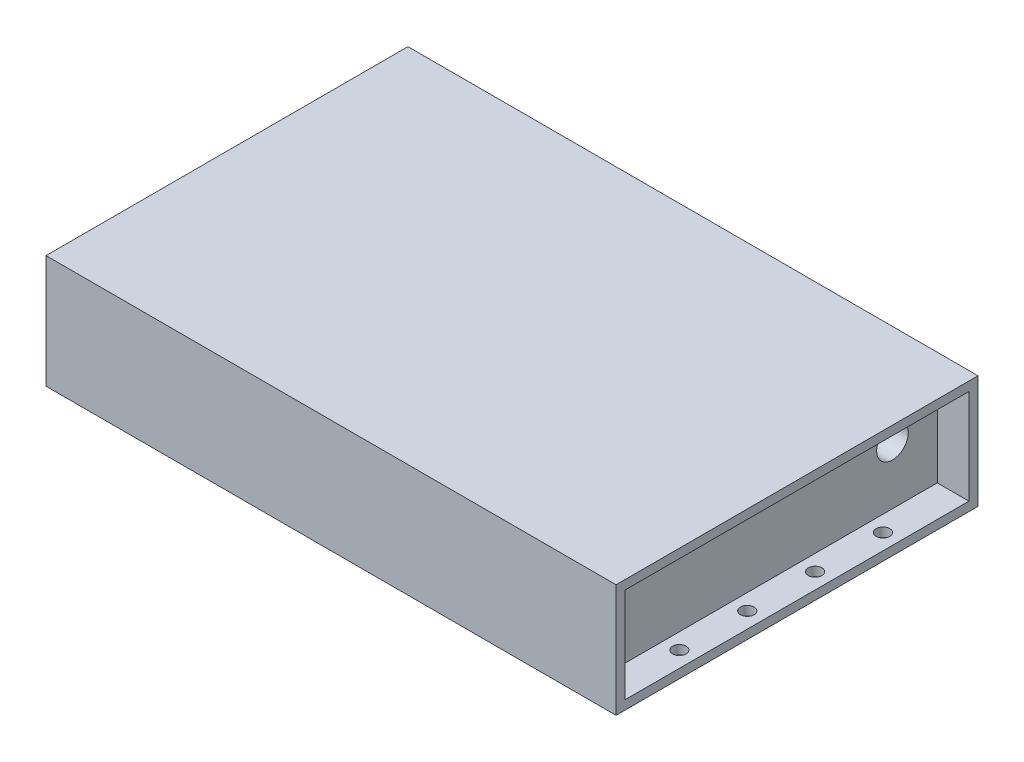
SolidWorks part; units mm, degrees
ref_plane "前视基准面" through (0, 0, 0) normal (0, 0, 1) x (1, 0, 0)
ref_plane "上视基准面" through (0, 0, 0) normal (0, 1, 0) x (1, 0, 0)
ref_plane "右视基准面" through (0, 0, 0) normal (1, 0, 0) x (0, 0, -1)
sketch "草图1" plane through (0, 0, 0) normal (0, 1, 0) x (1, 0, 0)
  line L1 (0, 0) -> (126, 0)
  line L2 (0, 0) -> (0, -80)
  line L3 (0, -80) -> (126, -80)
  line L4 (126, 0) -> (126, -80)
extrude "凸台-拉伸1" add sketch "草图1" along normal blind 25
sketch "草图2" plane through (126, 0, 0) normal (1, 0, 0) x (0, 0, -1)
  line L1 (-78, 23) -> (-2, 23)
  line L2 (-78, 23) -> (-78, 2)
  line L3 (-78, 2) -> (-2, 2)
  line L4 (-2, 23) -> (-2, 2)
  line L5 (-80, 25) -> (-80, 0) construction
  line L6 (0, 25) -> (0, 0) construction
  line L7 (-80, 25) -> (0, 25) construction
  line L8 (-80, 0) -> (0, 0) construction
  dimension "D1" = 2
  dimension "D2" = 2
  dimension "D3" = 2
  dimension "D4" = 2
extrude "切除-拉伸1" cut sketch "草图2" against normal blind 7
sketch "草图3" plane through (0, 0, 0) normal (-1, 0, 0) x (0, 0, 1)
  line L0 (0, 25) -> (0, 0) construction
  line L1 (2, 23) -> (78, 23)
  line L2 (2, 23) -> (2, 2)
  line L3 (2, 2) -> (78, 2)
  line L4 (78, 23) -> (78, 2)
  line L5 (80, 25) -> (80, 0) construction
  line L6 (0, 25) -> (80, 25) construction
  line L7 (0, 0) -> (80, 0) construction
  dimension "D1" = 2
  dimension "D2" = 2
  dimension "D3" = 2
  dimension "D4" = 2
extrude "切除-拉伸2" cut sketch "草图3" against normal blind 7
sketch "草图4" plane through (119, 0, 0) normal (1, 0, 0) x (0, 0, -1)
  circle A0 centre (-11.9052, 14.8414) radius 3.5
extrude "切除-拉伸3" cut sketch "草图4" against normal blind 7
sketch "草图5" plane through (0, 2, 0) normal (0, 1, 0) x (1, 0, 0)
  line L0 (119, -2) -> (126, -2) construction
  line L2 (119, -2) -> (126, -2) construction
  line L3 (122.5, -2) -> (122.5, -78) construction
  circle A0 centre (122.5, -17.5) radius 1.5
  circle A1 centre (122.5, -32.5) radius 1.5
  circle A2 centre (122.5, -47.5) radius 1.5
  circle A3 centre (122.5, -62.5) radius 1.5
  dimension "D1" = 15.5
  dimension "D2" = 15
  dimension "D3" = 15
  dimension "D4" = 15
  dimension "D5" = 15.5
extrude "切除-拉伸5" cut sketch "草图5" against normal blind 23
sketch "草图6" plane through (0, 2, 0) normal (0, 1, 0) x (1, 0, 0)
  line L0 (3.5, -2) -> (3.5, -78) construction
  line L1 (7, -2) -> (0, -2) construction
  line L2 (7, -78) -> (0, -78) construction
  circle A0 centre (3.5, -17.5) radius 1.5
  circle A1 centre (3.5, -32.5) radius 1.5
  circle A2 centre (3.5, -47.5) radius 1.5
  circle A3 centre (3.5, -62.5) radius 1.5
  dimension "D1" = 15.5
  dimension "D2" = 15
  dimension "D3" = 15
  dimension "D4" = 15
extrude "切除-拉伸6" cut sketch "草图6" against normal blind 23
sketch "草图7" plane through (0, 0, 0) normal (0, -1, 0) x (1, 0, 0)
  line L0 (63, 87.7011) -> (63, -8.4553)
